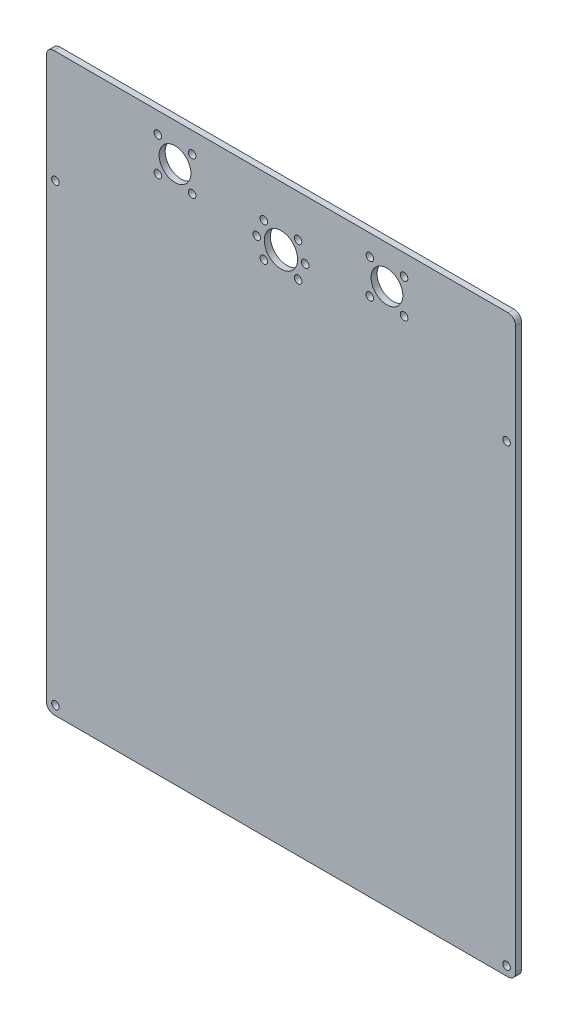
SolidWorks part; units mm, degrees
ref_plane "Plan de face" through (0, 0, 0) normal (0, 0, 1) x (1, 0, 0)
ref_plane "Plan de dessus" through (0, 0, 0) normal (0, 1, 0) x (1, 0, 0)
ref_plane "Plan de droite" through (0, 0, 0) normal (1, 0, 0) x (0, 0, -1)
sketch "Esquisse1" plane through (0, 0, 0) normal (0, 0, 1) x (1, 0, 0)
  line L0 (-19.0607, -18.2743) -> (290.9393, -18.2743) construction
  line L1 (-19.0607, 17.2124) -> (290.9393, 17.2124)
  line L2 (-19.0607, 17.2124) -> (-19.0607, -362.7876)
  line L3 (-19.0607, -362.7876) -> (290.9393, -362.7876)
  line L4 (290.9393, 17.2124) -> (290.9393, -362.7876)
  dimension "D1" = 380
  dimension "D2" = 310
extrude "Boss.-Extru.1" add sketch "Esquisse1" along normal blind 4
sketch "Esquisse3" plane through (0, 0, 0) normal (0, 0, -1) x (-1, 0, 0)
  line L0 (-135.9393, -362.7876) -> (-135.9393, 17.2124) construction
  line L1 (-290.9393, -362.7876) -> (-290.9393, 17.2124) construction
  line L2 (13.0607, -56.7876) -> (-284.9393, -56.7876)
  line L3 (13.0607, -56.7876) -> (13.0607, -356.7876)
  line L4 (13.0607, -356.7876) -> (-284.9393, -356.7876)
  line L5 (-284.9393, -56.7876) -> (-284.9393, -356.7876)
  line L6 (19.0607, 17.2124) -> (19.0607, -362.7876) construction
  line L7 (-290.9393, 17.2124) -> (19.0607, 17.2124) construction
  line L8 (19.0607, -362.7876) -> (-290.9393, -362.7876) construction
  line L9 (-284.9393, -337.7876) -> (13.0607, -337.7876) construction
  line L10 (-290.9393, -172.7876) -> (19.0607, -172.7876) construction
  line L11 (-77.253, -326.4739) -> (-54.6256, -326.4739)
  line L12 (-77.253, -326.4739) -> (-77.253, -349.1013)
  line L13 (-77.253, -349.1013) -> (-54.6256, -349.1013)
  line L14 (-54.6256, -326.4739) -> (-54.6256, -349.1013)
  line L15 (-77.253, -326.4739) -> (-54.6256, -349.1013) construction
  line L16 (-77.253, -349.1013) -> (-54.6256, -326.4739) construction
  line L17 (-217.253, -326.4739) -> (-194.6256, -326.4739)
  line L18 (-217.253, -326.4739) -> (-217.253, -349.1013)
  line L19 (-217.253, -349.1013) -> (-194.6256, -349.1013)
  line L20 (-194.6256, -326.4739) -> (-194.6256, -349.1013)
  line L21 (-217.253, -326.4739) -> (-194.6256, -349.1013) construction
  line L22 (-217.253, -349.1013) -> (-194.6256, -326.4739) construction
  line L23 (-124.6256, -10.4739) -> (-147.253, -33.1013) construction
  line L24 (-124.6256, -312.4739) -> (-147.253, -335.1013) construction
  line L25 (-124.6256, -335.1013) -> (-147.253, -312.4739) construction
  line L26 (-124.6256, -33.1013) -> (-147.253, -10.4739) construction
  line L27 (-217.253, 3.5261) -> (-194.6256, -19.1013) construction
  line L28 (-217.253, -19.1013) -> (-194.6256, 3.5261) construction
  line L29 (-77.253, 3.5261) -> (-54.6256, -19.1013) construction
  line L30 (-77.253, -19.1013) -> (-54.6256, 3.5261) construction
  line L31 (-194.6256, -19.1013) -> (-194.6256, 3.5261)
  line L32 (-217.253, 3.5261) -> (-194.6256, 3.5261)
  line L33 (-217.253, -19.1013) -> (-217.253, 3.5261)
  line L34 (-217.253, -19.1013) -> (-194.6256, -19.1013)
  line L35 (-54.6256, -19.1013) -> (-54.6256, 3.5261)
  line L36 (-77.253, 3.5261) -> (-54.6256, 3.5261)
  line L37 (-77.253, -19.1013) -> (-77.253, 3.5261)
  line L38 (-77.253, -19.1013) -> (-54.6256, -19.1013)
  circle A0 centre (-205.9393, -337.7876) radius 10.5
  circle A1 centre (-147.253, -10.4739) radius 2.5
  circle A2 centre (-65.9393, -337.7876) radius 10.5
  circle A3 centre (13.0607, -356.7876) radius 2.5
  circle A4 centre (-284.9393, -356.7876) radius 2.5
  circle A5 centre (-284.9393, -56.7876) radius 2.5
  circle A6 centre (13.0607, -56.7876) radius 2.5
  circle A7 centre (-65.9393, -337.7876) radius 16
  circle A8 centre (-205.9393, -337.7876) radius 16
  circle A9 centre (-77.253, -349.1013) radius 2.5
  circle A10 centre (-77.253, -326.4739) radius 2.5
  circle A11 centre (-54.6256, -326.4739) radius 2.5
  circle A12 centre (-54.6256, -349.1013) radius 2.5
  circle A13 centre (-217.253, -349.1013) radius 2.5
  circle A14 centre (-217.253, -326.4739) radius 2.5
  circle A15 centre (-194.6256, -326.4739) radius 2.5
  circle A16 centre (-194.6256, -349.1013) radius 2.5
  circle A17 centre (-124.6256, -10.4739) radius 2.5
  circle A18 centre (-124.6256, -33.1013) radius 2.5
  circle A19 centre (-147.253, -33.1013) radius 2.5
  circle A20 centre (-119.9393, -21.7876) radius 2.5
  circle A21 centre (-151.9393, -21.7876) radius 2.5
  circle A22 centre (-135.9393, -21.7876) radius 16
  circle A23 centre (-135.9393, -21.7876) radius 11
  circle A24 centre (-135.9393, -323.7876) radius 11
  circle A25 centre (-135.9393, -323.7876) radius 16
  circle A26 centre (-151.9393, -323.7876) radius 2.5
  circle A27 centre (-119.9393, -323.7876) radius 2.5
  circle A28 centre (-147.253, -312.4739) radius 2.5
  circle A29 centre (-124.6256, -312.4739) radius 2.5
  circle A30 centre (-124.6256, -335.1013) radius 2.5
  circle A31 centre (-147.253, -335.1013) radius 2.5
  circle A32 centre (-194.6256, 3.5261) radius 2.5
  circle A33 centre (-194.6256, -19.1013) radius 2.5
  circle A34 centre (-217.253, -19.1013) radius 2.5
  circle A35 centre (-217.253, 3.5261) radius 2.5
  circle A36 centre (-54.6256, 3.5261) radius 2.5
  circle A37 centre (-54.6256, -19.1013) radius 2.5
  circle A38 centre (-77.253, -19.1013) radius 2.5
  circle A39 centre (-77.253, 3.5261) radius 2.5
  circle A40 centre (-205.9393, -7.7876) radius 16
  circle A41 centre (-65.9393, -7.7876) radius 16
  circle A42 centre (-65.9393, -7.7876) radius 10.5
  circle A43 centre (-205.9393, -7.7876) radius 10.5
  point P74 (-135.9393, -323.7876)
  point P75 (-135.9393, -323.7876)
  dimension "D3" = 5
  dimension "D9" = 21
  dimension "D10" = 21
  dimension "D12" = 32
  dimension "D13" = 32
  dimension "D14" = 5
  dimension "D19" = 5
  dimension "D1" = 6
  dimension "D2" = 6
  dimension "D4" = 6
  dimension "D5" = 85
  dimension "D6" = 85
  dimension "D7" = 300
  dimension "D8" = 25
  dimension "D11" = 14
fillet "Congé1" radius 5 4 edges at (290.9393, 17.2124, 2) (-19.0607, 17.2124, 2) (-19.0607, -362.7876, 2) (290.9393, -362.7876, 2)
extrude "Enlèv. mat.-Extru.1" cut sketch "Esquisse3" against normal blind 10 contours A43 | A23 | A42 | A35 | A32 | A33 | A34 | A39 | A36 | A37 | A38 | A20 | A17 | A18 | A19 | A21 | A1 | A6 | A3 | A4 | A5
equation "\"D2@Esquisse3\"=\"D1@Esquisse3\""
equation "\"D4@Esquisse3\"=\"D1@Esquisse3\""
equation "\"D6@Esquisse3\"=\"D5@Esquisse3\""
equation "\"D13@Esquisse3\"=\"D12@Esquisse3\""
